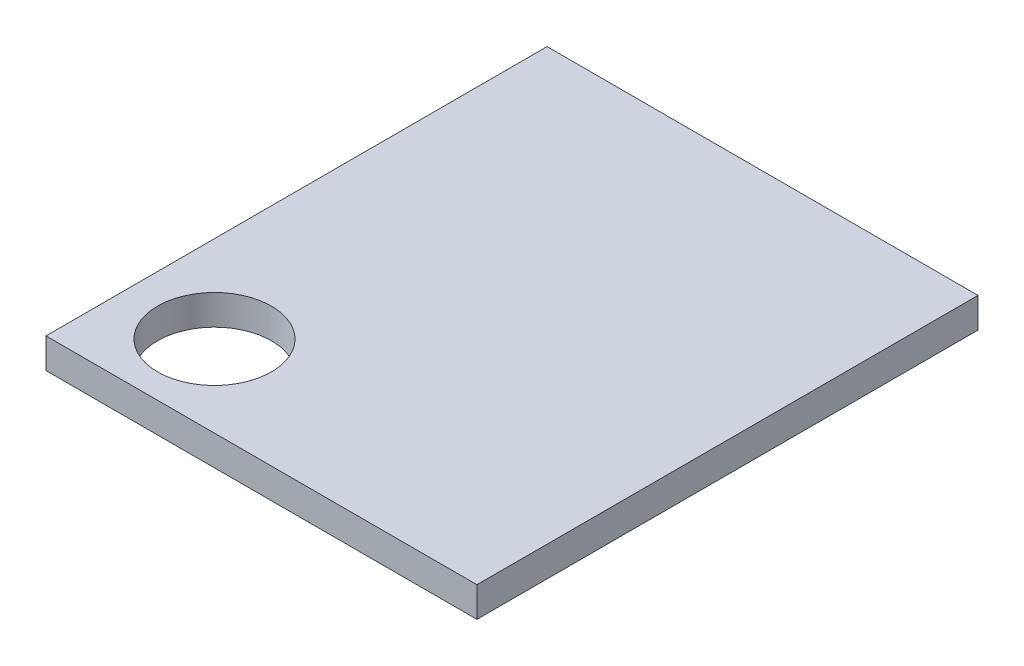
SolidWorks part; units mm, degrees
ref_plane "Front Plane" through (0, 0, 0) normal (0, 0, 1) x (1, 0, 0)
ref_plane "Top Plane" through (0, 0, 0) normal (0, 1, 0) x (1, 0, 0)
ref_plane "Right Plane" through (0, 0, 0) normal (1, 0, 0) x (0, 0, -1)
sketch "Esquisse3" plane through (0, 0, 0) normal (0, 0, 1) x (1, 0, 0)
  line L1 (0, 0) -> (215, 0)
  line L2 (0, 0) -> (0, 15)
  line L3 (0, 15) -> (215, 15)
  line L4 (215, 0) -> (215, 15)
  dimension "D1" = 15
  dimension "D2" = 215
extrude "Boss.-Extru.2" add sketch "Esquisse3" along normal blind 250
sketch "Esquisse4" plane through (0, 15, 0) normal (0, 1, 0) x (1, 0, 0)
  circle A0 centre (43.3628, -209.2973) radius 28.4299
extrude "Enlèv. mat.-Extru.1" cut sketch "Esquisse4" against normal blind 250
